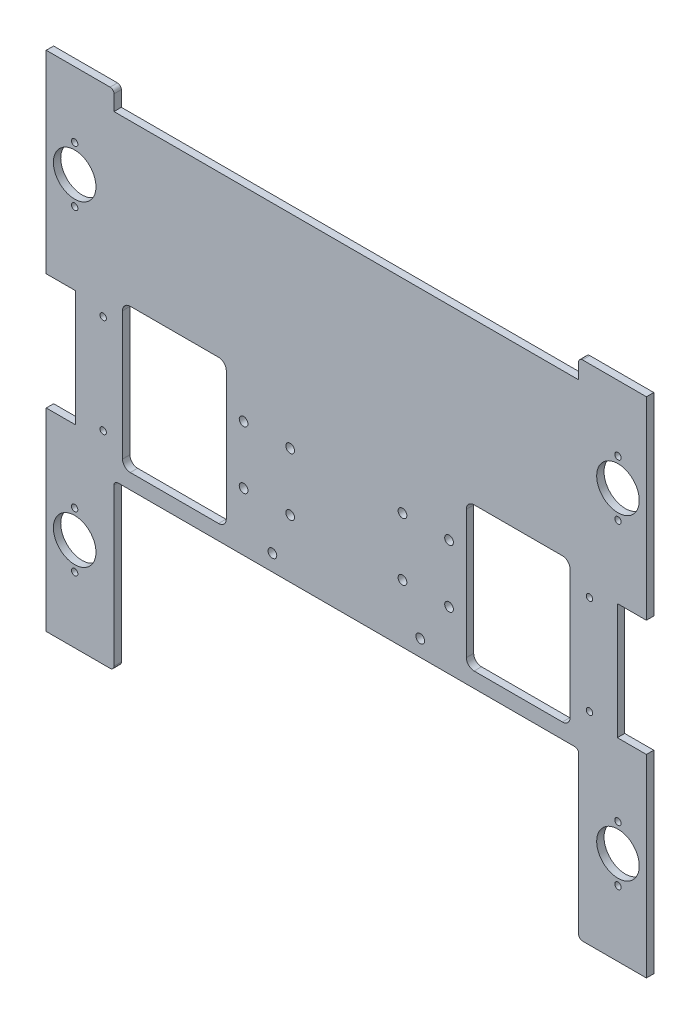
SolidWorks part; units mm, degrees
ref_plane "Front Plane" through (0, 0, 0) normal (0, 0, 1) x (1, 0, 0)
ref_plane "Top Plane" through (0, 0, 0) normal (0, 1, 0) x (1, 0, 0)
ref_plane "Right Plane" through (0, 0, 0) normal (1, 0, 0) x (0, 0, -1)
ref_plane "Plane1" through (0, 150, 0) normal (0, 1, 0) x (1, 0, 0)
ref_plane "Plane2" through (0, -150, 0) normal (0, 1, 0) x (1, 0, 0)
ref_plane "Plane3" through (150, 0, 0) normal (1, 0, 0) x (0, 0, -1)
ref_plane "Plane4" through (-150, 0, 0) normal (1, 0, 0) x (0, 0, -1)
sketch "Sketch2" plane through (0, 0, 0) normal (0, 0, 1) x (1, 0, 0)
  line L0 (0, -10.2) -> (0, 50.0764) construction
  line L5 (-53.06, 39.945) -> (-53.06, 10.055) construction
  line L23 (-155, 155) -> (-122, 155)
  line L24 (139.6652, 116) -> (168.3348, 116) construction
  line L31 (-155, -105) -> (-122, -105)
  line L40 (-152.1866, -81.0661) -> (-123.5266, -81.0661) construction
  line L42 (-120, 153) -> (-120, 145.0725)
  line L43 (-120, 145.0725) -> (120, 145.0725)
  line L47 (-66, 62.1714) -> (-111.5977, 62.1714)
  line L48 (66, 62.1714) -> (111.5977, 62.1714)
  line L49 (62, 58.1714) -> (62, -8.1714)
  line L50 (66, -12.1714) -> (111.5977, -12.1714)
  line L51 (115.5977, 58.1714) -> (115.5977, -8.1714)
  line L52 (62, 62.1714) -> (115.5977, -12.1714) construction
  line L53 (62, -12.1714) -> (115.5977, 62.1714) construction
  line L54 (-62, 58.1714) -> (-62, -8.1714)
  line L55 (-66, -12.1714) -> (-111.5977, -12.1714)
  line L56 (-115.5977, 58.1714) -> (-115.5977, -8.1714)
  line L57 (177.1787, -66.0847) -> (177.1787, 11.9153) construction
  line L70 (-125.5977, 50.5) -> (-125.5977, -0.5) construction
  line L73 (-155, 155) -> (-155, 55)
  line L74 (162.5, 25) -> (139.6652, 25) construction
  line L75 (-120, -103) -> (-120, -22)
  line L76 (-118, -20) -> (118, -20)
  line L79 (-155, -5) -> (-155, -105)
  line L80 (-155, -5) -> (-140, -5)
  line L82 (-155, 55) -> (-140, 55)
  line L83 (-140, -5) -> (-140, 55)
  line L84 (-145.4163, 25) -> (-140, 55) construction
  line L85 (-145.4163, 25) -> (-140, -5) construction
  line L88 (145.4163, 25) -> (140, -5) construction
  line L89 (145.4163, 25) -> (140, 55) construction
  line L90 (125.5977, 50.5) -> (125.5977, -0.5) construction
  line L91 (140, -5) -> (140, 55)
  line L92 (155, 55) -> (140, 55)
  line L93 (155, -5) -> (140, -5)
  line L94 (155, -5) -> (155, -105)
  line L95 (155, 155) -> (155, 55)
  line L96 (120, -103) -> (120, -22)
  line L97 (155, -105) -> (122, -105)
  line L98 (155, 155) -> (122, 155)
  line L99 (120, 153) -> (120, 145.0725)
  circle A1 centre (-140.3098, 121.0768) radius 1.65
  circle A2 centre (-140.3098, 92.4072) radius 1.65
  circle A3 centre (140.3098, 121.0768) radius 1.65
  circle A4 centre (140.3098, 92.4072) radius 1.65
  circle A9 centre (140.3098, 106.742) radius 11
  circle A10 centre (-140.3098, 106.742) radius 11
  circle A17 centre (125.5977, -0.5) radius 1.65
  circle A18 centre (125.5977, 50.5) radius 1.65
  circle A19 centre (-125.5977, -0.5) radius 1.65
  circle A20 centre (-125.5977, 50.5) radius 1.65
  circle A27 centre (-29, 10.055) radius 2.25
  circle A32 centre (-29, 39.945) radius 2.25
  circle A33 centre (-53.06, 39.945) radius 2.25
  circle A34 centre (-53.06, 10.055) radius 2.25
  circle A35 centre (53.06, 10.055) radius 2.25
  circle A36 centre (29, 10.055) radius 2.25
  circle A37 centre (29, 39.945) radius 2.25
  circle A38 centre (53.06, 39.945) radius 2.25
  arc A47 (-120, 153) -> (-122, 155) centre (-122, 153) ccw
  arc A48 (62, -8.1714) -> (66, -12.1714) centre (66, -8.1714) ccw
  arc A49 (111.5977, -12.1714) -> (115.5977, -8.1714) centre (111.5977, -8.1714) ccw
  arc A50 (111.5977, 62.1714) -> (115.5977, 58.1714) centre (111.5977, 58.1714) cw
  arc A51 (66, 62.1714) -> (62, 58.1714) centre (66, 58.1714) ccw
  arc A52 (-111.5977, 62.1714) -> (-115.5977, 58.1714) centre (-111.5977, 58.1714) ccw
  arc A53 (-66, 62.1714) -> (-62, 58.1714) centre (-66, 58.1714) cw
  arc A54 (-62, -8.1714) -> (-66, -12.1714) centre (-66, -8.1714) cw
  arc A55 (-111.5977, -12.1714) -> (-115.5977, -8.1714) centre (-111.5977, -8.1714) cw
  circle A68 centre (140.3098, -71.0768) radius 1.65
  circle A69 centre (140.3098, -42.4072) radius 1.65
  circle A70 centre (140.3098, -56.742) radius 11
  circle A71 centre (-140.3098, -56.742) radius 11
  circle A72 centre (-140.3098, -42.4072) radius 1.65
  circle A73 centre (-140.3098, -71.0768) radius 1.65
  arc A76 (-120, -22) -> (-118, -20) centre (-118, -22) cw
  arc A77 (-120, -103) -> (-122, -105) centre (-122, -103) cw
  arc A79 (120, -22) -> (118, -20) centre (118, -22) ccw
  arc A80 (120, -103) -> (122, -105) centre (122, -103) ccw
  arc A81 (120, 153) -> (122, 155) centre (122, 153) cw
  circle A82 centre (38.1799, -11.5638) radius 2.25
  circle A83 centre (-38.1799, -11.5638) radius 2.25
  point P0 (0, 0)
  point P2 (0, 0)
  point P4 (0, 150)
  point P7 (-145.4163, 25)
  point P11 (-125.5977, 25)
  point P12 (88.7989, 25)
  point P23 (-53.06, 25)
  point P24 (0, -20)
  point P33 (-140, 25)
  point P82 (177.1787, -27.0847)
  point P111 (-115.5977, 25)
  point P112 (145.4163, 25)
  point P122 (0, 145.0725)
  point P132 (-62, 25)
  dimension "D3" = 51
  dimension "D7" = 155
  dimension "D8" = 3.3
  dimension "D9" = 120
  dimension "D10" = 22
  dimension "D11" = 74.3428
  dimension "D13" = 53.5977
  dimension "D16" = 62
  dimension "D17" = 15
  dimension "D18" = 60
  dimension "D19" = 3.3
  dimension "D6" = 14.3348
  dimension "D20" = 14.3348
  dimension "D21" = 130
  dimension "D23" = 4.5
  dimension "D24" = 45
  dimension "D25" = 4.5
  dimension "D26" = 4.5
  dimension "D27" = 29.89
  dimension "D29" = 24.06
  dimension "D31" = 4
  dimension "D32" = 130
  dimension "D4" = 3.3
  dimension "D5" = 10
  dimension "D22" = 29.89
  dimension "D28" = 24.06
  dimension "D30" = 29
  dimension "D14" = 2
extrude "Boss-Extrude1" add sketch "Sketch2" along normal blind 3.8
